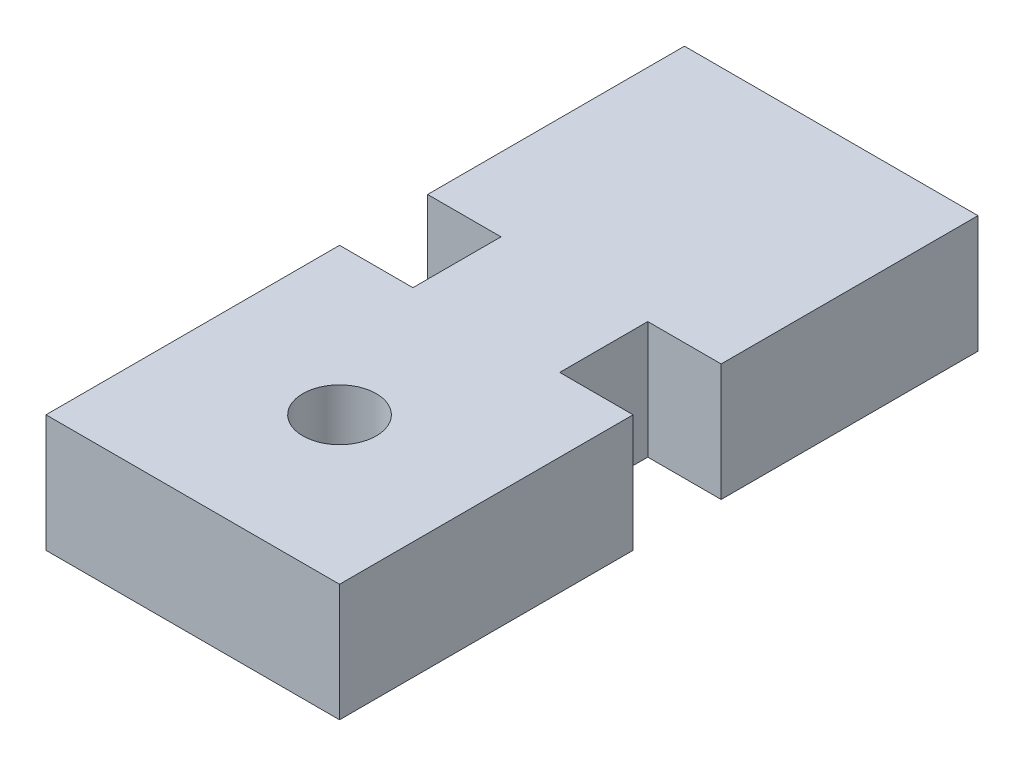
SolidWorks part; units mm, degrees
ref_plane "Plano frontal" through (0, 0, 0) normal (0, 0, 1) x (1, 0, 0)
ref_plane "Plano superior" through (0, 0, 0) normal (0, 1, 0) x (1, 0, 0)
ref_plane "Plano direito" through (0, 0, 0) normal (1, 0, 0) x (0, 0, -1)
sketch "Sketch1" plane through (0, 0, 0) normal (0, 1, 0) x (1, 0, 0)
  line L1 (-5, 5) -> (5, 5)
  line L2 (-5, 5) -> (-5, -5)
  line L3 (-5, -5) -> (5, -5)
  line L4 (5, 5) -> (5, -5)
  circle A0 centre (0, 0) radius 1.25
  point P7 (-5, 0)
  point P8 (0, 5)
  dimension "D1" = 2.5
  dimension "D4" = 3.75
  dimension "D2" = 10
  dimension "D3" = 10
extrude "Boss-Extrude1" add sketch "Sketch1" along normal mid plane 4
sketch "Sketch2" plane through (0, 0, 0) normal (0, 1, 0) x (1, 0, 0)
  line L0 (5, 5) -> (-5, 5) construction
  line L1 (-2.5, 5) -> (2.5, 5)
  line L2 (-2.5, 5) -> (-2.5, 8)
  line L3 (-2.5, 8) -> (2.5, 8)
  line L4 (2.5, 5) -> (2.5, 8)
  point P6 (0, 5)
  dimension "D1" = 5
  dimension "D2" = 3
extrude "Boss-Extrude2" add sketch "Sketch2" along normal mid plane 4
sketch "Sketch3" plane through (0, 0, 0) normal (0, 1, 0) x (1, 0, 0)
  line L0 (2.5, 8) -> (-2.5, 8) construction
  line L1 (-5, 16.75) -> (5, 16.75)
  line L2 (-5, 16.75) -> (-5, 8)
  line L3 (-5, 8) -> (5, 8)
  line L4 (5, 16.75) -> (5, 8)
  line L5 (-5, 5) -> (-5, -5) construction
  line L6 (5, -5) -> (5, 5) construction
  dimension "D1" = 8.75
extrude "Boss-Extrude3" add sketch "Sketch3" along normal mid plane 4
